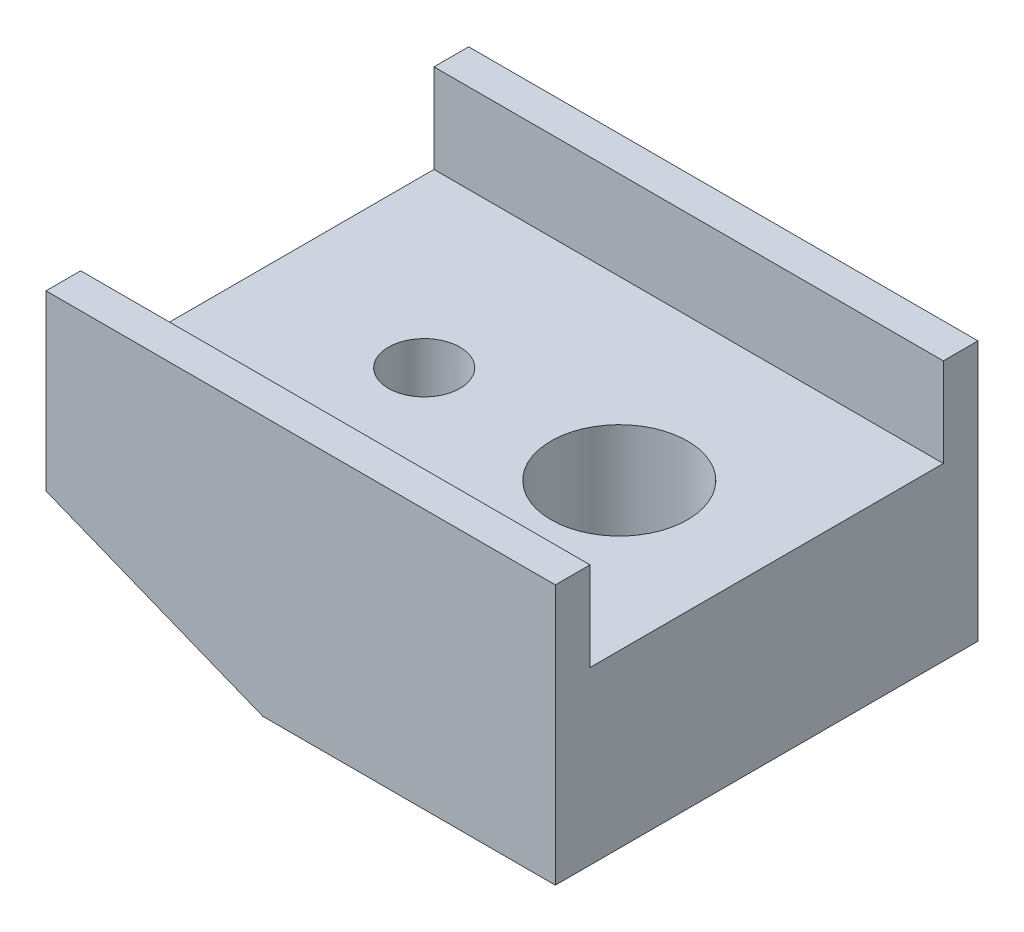
SolidWorks part; units mm, degrees
ref_plane "Front" through (0, 0, 0) normal (0, 0, 1) x (1, 0, 0)
ref_plane "Top" through (0, 0, 0) normal (0, 1, 0) x (1, 0, 0)
ref_plane "Right" through (0, 0, 0) normal (1, 0, 0) x (0, 0, -1)
sketch "Sketch1" plane through (0, 0, 0) normal (0, 0, 1) x (1, 0, 0)
  line L0 (-13.5, 0) -> (-23.5, 4)
  line L1 (0, 0) -> (-13.5, 0)
  line L2 (0, 0) -> (0, 12)
  line L3 (0, 12) -> (-23.5, 12)
  line L4 (-23.5, 4) -> (-23.5, 12)
  point P6 (-23.5, 0)
  dimension "D1" = 12
  dimension "D2" = 10
  dimension "D3" = 4
  dimension "D4" = 23.5
extrude "Extrude1" add sketch "Sketch1" along normal blind 19.5
sketch "Sketch2" plane through (0, 0, 0) normal (1, 0, 0) x (0, 0, -1)
  line L0 (-17.9, 12) -> (-17.9, 7.9)
  line L1 (0, 12) -> (-19.5, 12) construction
  line L2 (-1.6, 7.9) -> (-17.9, 7.9)
  line L3 (-1.6, 0) -> (-1.6, 12)
  line L4 (0, 0) -> (0, 12)
  line L5 (0, 12) -> (-19.5, 12)
  line L6 (-19.5, 12) -> (-19.5, 0)
  line L7 (-19.5, 0) -> (0, 0)
  line L8 (0, 0) -> (0, 12)
  line L9 (-1.6, 12) -> (-17.9, 12)
  line L10 (-19.5, 12) -> (-19.5, 0)
  line L11 (-19.5, 0) -> (0, 0)
  line L12 (-1.6, 7.9) -> (-1.6, 12)
  line L13 (0, 7.9) -> (-19.5, 7.9) construction
  line L14 (-17.9, 12) -> (-17.9, 0) construction
  line M7 (0, 12) -> (-19.5, 12)
  dimension "D1" = 0
  dimension "D2" = 1.6
extrude "Cut-Extrude1" cut sketch "Sketch2" against normal through all contours L2 L12 L0 M7
sketch "Sketch3" plane through (0, 7.9, 0) normal (0, 1, 0) x (-1, 0, 0)
  line L0 (0, 9.75) -> (6.8, 9.75) construction
  line L1 (0, 1.6) -> (0, 17.9) construction
  line L2 (6.8, 9.75) -> (15.8, 9.75) construction
  dimension "D1" = 6.8
  dimension "D2" = 9
hole_wizard "M6.3 (6.3) Diameter Hole1" positions "3DSketch2" profile "Sketch5" hole size "M6.3" standard "Ansi Metric" end condition through all
sketch3d "3DSketch2"
  point P0 (-6.8, 7.9, 9.75)
sketch "Sketch5" plane through (-6.8, 7.9, 9.75) normal (1, 0, 0) x (0, 0, 1)
  line L0 (0, 0) -> (0, 7.9)
  line L1 (0, 7.9) -> (3.15, 7.9)
  line L2 (3.15, 7.9) -> (3.15, 0)
  line L5 (3.15, 0) -> (0, 0)
  line L11 (0, -6.35) -> (0, 107.95) construction
  dimension "Thru Hole Dia." = 6.3
  dimension "Thru Hole Depth" = 7.9
hole_wizard "M4x0.7 Tapped Hole1" positions "3DSketch4" profile "Sketch7" tap size "M4x0.7" standard "Ansi Metric"
sketch3d "3DSketch4"
  point P0 (-15.8, 7.9, 9.75)
sketch "Sketch7" plane through (-15.8, 7.9, 9.75) normal (1, 0, 0) x (0, 0, 1)
  line L0 (0, 0) -> (0, 11.0914)
  line L1 (0, 11.0914) -> (1.65, 10.1)
  line L2 (1.65, 10.1) -> (1.65, 0)
  line L5 (1.65, 0) -> (0, 0)
  line L10 (0, 11.0914) -> (-1.65, 10.1) construction
  line L11 (0, -6.35) -> (0, 107.95) construction
  dimension "Tap Drill Dia." = 3.3
  dimension "Tap Drill Depth" = 10.1
  dimension "Drill Angle" = 118
cosmetic thread "Hole Thread1" parameters "D1"=7.64, "D2"=4
